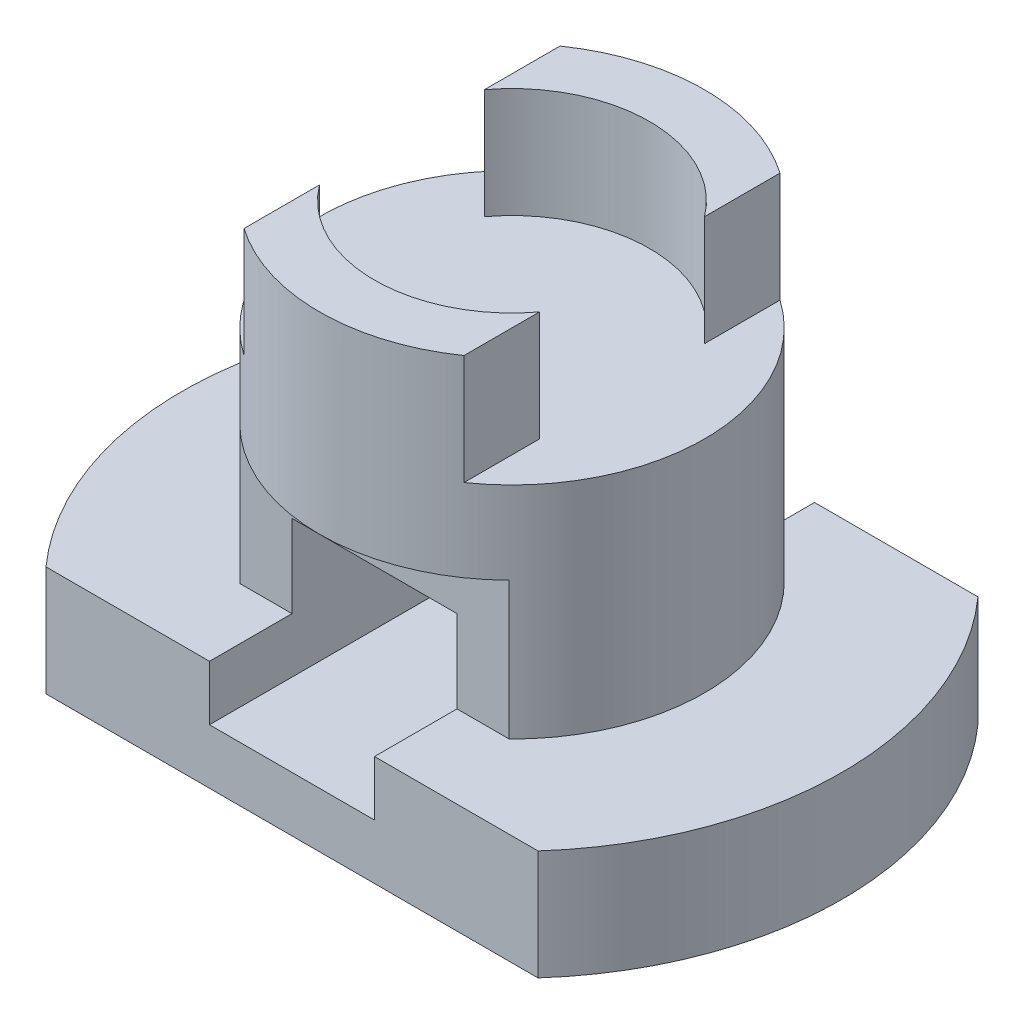
SolidWorks part; units mm, degrees
ref_plane "Front Plane" through (0, 0, 0) normal (0, 0, 1) x (1, 0, 0)
ref_plane "Top Plane" through (0, 0, 0) normal (0, 1, 0) x (1, 0, 0)
ref_plane "Right Plane" through (0, 0, 0) normal (1, 0, 0) x (0, 0, -1)
sketch "Sketch1" plane through (0, 0, 0) normal (0, 1, 0) x (1, 0, 0)
  line L1 (-44.7214, -40) -> (44.7214, -40)
  line L3 (-44.7214, 40) -> (44.7214, 40)
  arc A0 (44.7214, -40) -> (44.7214, 40) centre (0, 0) ccw
  arc A1 (-44.7214, 40) -> (-44.7214, -40) centre (0, 0) ccw
extrude "Boss-Extrude1" add sketch "Sketch1" along normal blind 20
sketch "Sketch2" plane through (0, 20, 0) normal (0, 1, 0) x (1, 0, 0)
  circle A0 centre (0, 0) radius 35
extrude "Boss-Extrude2" add sketch "Sketch2" along normal blind 40
sketch "Sketch3" plane through (0, 0, 40) normal (0, 0, 1) x (1, 0, 0)
  line L0 (-44.7214, 0) -> (44.7214, 0) construction
  line L1 (-15, 35) -> (15, 35)
  line L2 (-15, 35) -> (-15, 10)
  line L3 (-15, 10) -> (15, 10)
  line L4 (15, 35) -> (15, 10)
  dimension "D1" = 25
  dimension "D2" = 30
  dimension "D3" = 10
  dimension "D4" = 15
extrude "Cut-Extrude1" cut sketch "Sketch3" against normal blind 128
sketch "Sketch4" plane through (0, 0, 40) normal (0, 0, 1) x (1, 0, 0)
  line L0 (44.7214, 20) -> (44.7214, 45)
  line L1 (-44.7214, 20) -> (-44.7214, 45)
  line L2 (-44.7214, 45) -> (44.7214, 45)
  line L3 (-44.7214, 20) -> (44.7214, 20)
extrude "Cut-Extrude2" cut sketch "Sketch4" against normal blind 15
ref_plane "Plane1" through (0, 0, 0) normal (0, 0, 1) x (1, 0, 0)
mirror "Mirror1" about plane through (0, 0, 0) normal (0, 0, 1) of "Cut-Extrude2"
sketch "Sketch6" plane through (0, 60, 0) normal (0, 1, 0) x (1, 0, 0)
  line L2 (-20, -28.7228) -> (-20, -15)
  line L3 (20, -28.7228) -> (20, -15)
  line L4 (-20, 15) -> (-20, 28.7228)
  line L5 (20, 15) -> (20, 28.7228)
  circle A0 centre (0, 0) radius 35
  arc A1 (-20, -15) -> (20, -15) centre (0, 0) ccw
  arc A3 (20, 15) -> (-20, 15) centre (0, 0) ccw
  circle M5 centre (0, 0) radius 35
extrude "Boss-Extrude3" add sketch "Sketch6" along normal blind 20 contours A3 L5 L4 M5 | A1 L2 L3 M5
